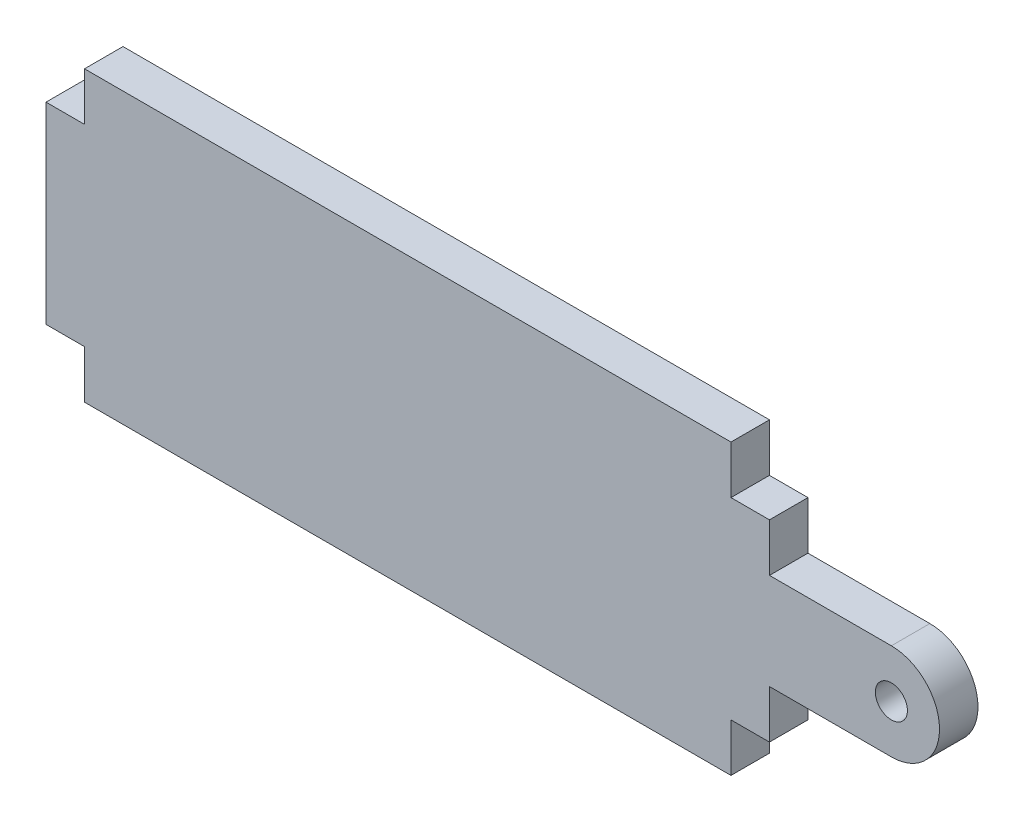
SolidWorks part; units mm, degrees
ref_plane "Front Plane" through (0, 0, 0) normal (0, 0, 1) x (1, 0, 0)
ref_plane "Top Plane" through (0, 0, 0) normal (0, 1, 0) x (1, 0, 0)
ref_plane "Right Plane" through (0, 0, 0) normal (1, 0, 0) x (0, 0, -1)
sketch "Sketch1" plane through (0, 0, 0) normal (0, 0, 1) x (1, 0, 0)
  line L0 (0, 9) -> (0, -9)
  line L1 (20.15, 9) -> (-20.15, 9)
  line L2 (20.15, 9) -> (20.15, -9)
  line L3 (20.15, -9) -> (-20.15, -9)
  line L4 (-20.15, 9) -> (-20.15, -9)
  line L5 (20.15, 9) -> (-20.15, -9) construction
  line L6 (20.15, -9) -> (-20.15, 9) construction
  line L7 (-20.15, 6) -> (-22.55, 6)
  line L9 (-20.15, -6) -> (-22.55, -6)
  line L10 (-22.55, 6) -> (-22.55, -6)
  line L11 (-20.15, 0) -> (-22.55, -6) construction
  line L12 (-20.15, 0) -> (-22.55, 6) construction
  line L13 (20.15, -6) -> (22.55, -6)
  line L14 (22.55, 3) -> (30.15, 3)
  line L16 (-22.55, 0) -> (-20.15, 0)
  line L17 (22.55, -3) -> (30.15, -3)
  line L18 (30.15, 3) -> (30.15, -3)
  line L19 (22.55, -0.72) -> (30.15, -3) construction
  line L20 (22.55, 0.72) -> (30.15, 3) construction
  line L21 (22.55, 6) -> (22.55, -6)
  line L22 (20.15, 6) -> (22.55, 6)
  line L23 (22.55, 0) -> (30.15, 0)
  circle A2 centre (30.15, 0) radius 3
  circle A3 centre (30.15, 0) radius 1
  point P0 (0, 0)
  point P6 (-20.15, 0)
  point P14 (20.15, 0)
extrude "Boss-Extrude1" add sketch "Sketch1" along normal blind 2.4
